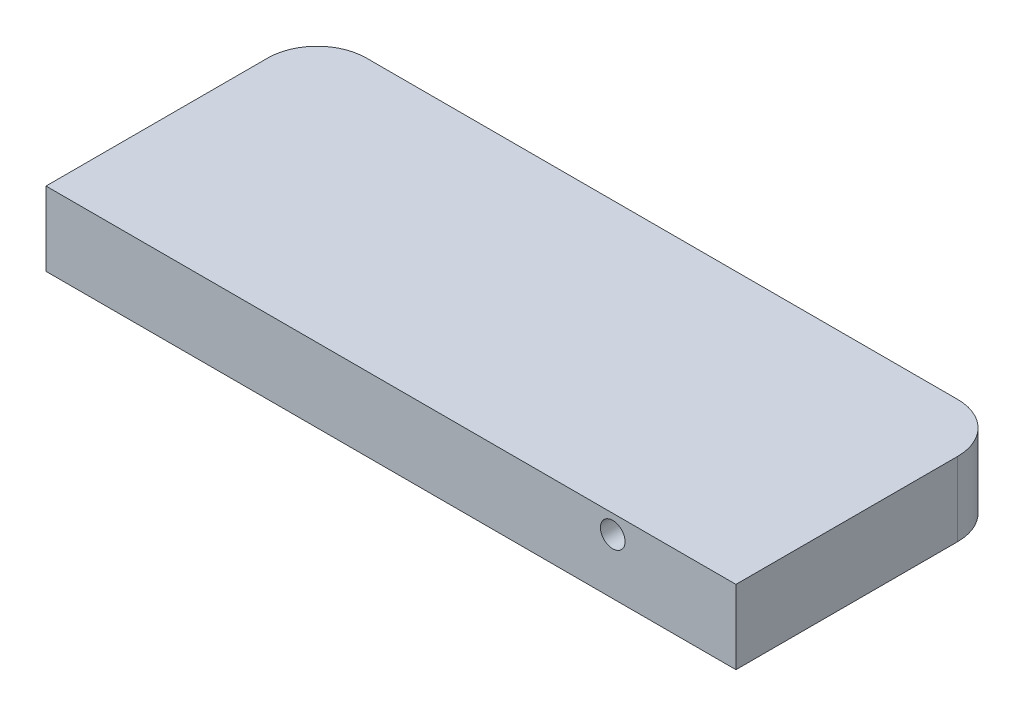
SolidWorks part; units mm, degrees
ref_plane "Plan de face" through (0, 0, 0) normal (0, 0, 1) x (1, 0, 0)
ref_plane "Plan de dessus" through (0, 0, 0) normal (0, 1, 0) x (1, 0, 0)
ref_plane "Plan de droite" through (0, 0, 0) normal (1, 0, 0) x (0, 0, -1)
sketch "Esquisse1" plane through (0, 0, 0) normal (0, 1, 0) x (1, 0, 0)
  line L1 (0, 0) -> (280, 0)
  line L2 (0, 0) -> (0, 90)
  line L3 (20, 110) -> (260, 110)
  line L4 (280, 0) -> (280, 90)
  arc A0 (260, 110) -> (280, 90) centre (260, 90) cw
  arc A1 (0, 90) -> (20, 110) centre (20, 90) cw
  point P7 (280, 110)
  point P10 (0, 110)
  dimension "D3" = 20
  dimension "D1" = 280
  dimension "D2" = 110
extrude "Boss.-Extru.1" add sketch "Esquisse1" against normal blind 30
sketch "Esquisse2" plane through (0, 0, 0) normal (0, 0, 1) x (1, 0, 0)
  line L0 (280, -30) -> (280, 0) construction
  line L1 (0, 0) -> (280, 0) construction
  circle A0 centre (230, -7.5) radius 5
  point P6 (0, 0)
  dimension "D1" = 10
  dimension "D2" = 50
  dimension "D3" = 7.5
extrude "Enlèv. mat.-Extru.1" cut sketch "Esquisse2" against normal blind 58
